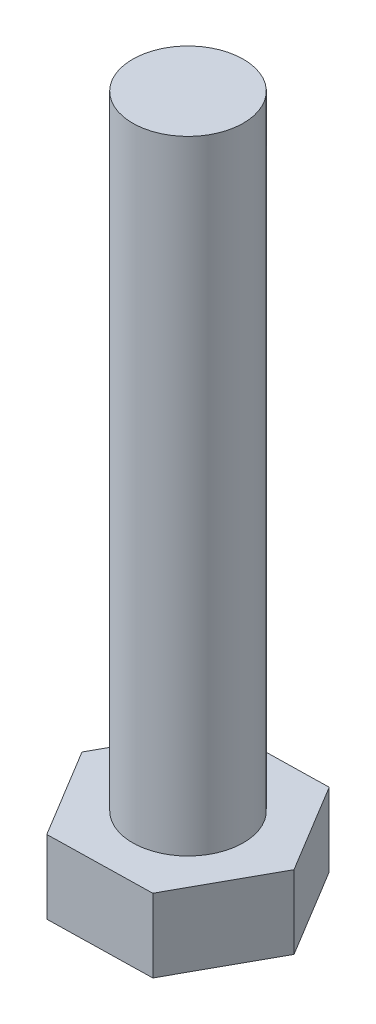
SolidWorks part; units mm, degrees
ref_plane "Front Plane" through (0, 0, 0) normal (0, 0, 1) x (1, 0, 0)
ref_plane "Top Plane" through (0, 0, 0) normal (0, 1, 0) x (1, 0, 0)
ref_plane "Right Plane" through (0, 0, 0) normal (1, 0, 0) x (0, 0, -1)
sketch "Sketch1" plane through (0, 0, 0) normal (0, 1, 0) x (1, 0, 0)
  line L1 (3.8835, -6.4227) -> (7.504, 0.1519)
  line L2 (7.504, 0.1519) -> (3.6205, 6.5746)
  line L3 (3.6205, 6.5746) -> (-3.8835, 6.4227)
  line L4 (-3.8835, 6.4227) -> (-7.504, -0.1519)
  line L5 (-7.504, -0.1519) -> (-3.6205, -6.5746)
  line L6 (-3.6205, -6.5746) -> (3.8835, -6.4227)
  circle A0 centre (0, 0) radius 6.5 construction
  dimension "D1" = 13
extrude "Boss-Extrude1" add sketch "Sketch1" along normal blind 5.3
sketch "Sketch2" plane through (0, 5.3, 0) normal (0, 1, 0) x (1, 0, 0)
  circle A0 centre (0, 0) radius 4
  dimension "D1" = 8
extrude "Boss-Extrude2" add sketch "Sketch2" along normal blind 45
